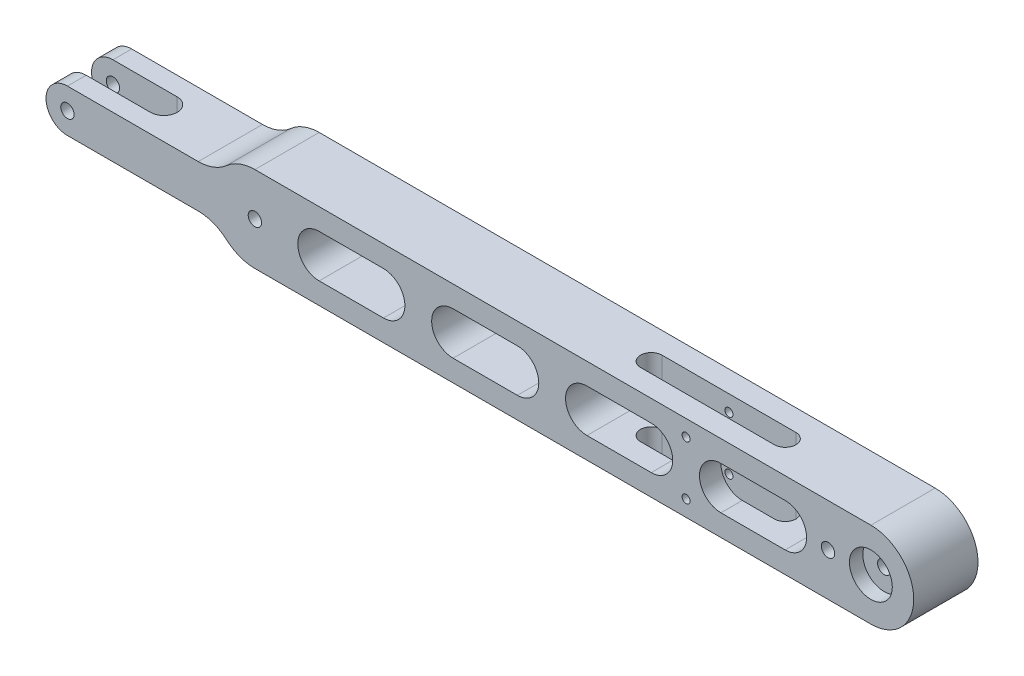
SolidWorks part; units mm, degrees
material "1060 Alloy"
ref_plane "前视基准面" through (0, 0, 0) normal (0, 0, 1) x (1, 0, 0)
ref_plane "上视基准面" through (0, 0, 0) normal (0, 1, 0) x (1, 0, 0)
ref_plane "右视基准面" through (0, 0, 0) normal (1, 0, 0) x (0, 0, -1)
sketch "Sketch1" plane through (0, 0, 0) normal (0, 0, 1) x (1, 0, 0)
  line L0 (0, 0) -> (-70, 0) construction
  line L1 (0, 0) -> (230, 0) construction
  line L2 (0, 16) -> (230, 16)
  line L4 (230, -16) -> (0, -16)
  line L5 (-70, 8) -> (-21.166, 8)
  line L6 (-70, -8) -> (-21.166, -8)
  arc A0 (-70, 8) -> (-70, -8) centre (-70, 0) ccw
  arc A1 (230, -16) -> (230, 16) centre (230, 0) ccw
  arc A2 (-10.583, -12) -> (0, -16) centre (0, 0) ccw
  arc A3 (-10.583, -12) -> (-21.166, -8) centre (-21.166, -24) ccw
  arc A4 (-21.166, 8) -> (-10.583, 12) centre (-21.166, 24) ccw
  arc A5 (0, 16) -> (-10.583, 12) centre (0, 0) ccw
  circle A6 centre (0, 0) radius 2.5
  circle A7 centre (-70, 0) radius 2.5
  point P6 (0, 0)
  dimension "D3" = 16
  dimension "D4" = 32
  dimension "D5" = 16
  dimension "D6" = 5
  dimension "D7" = 5
  dimension "D2" = 230
  dimension "D1" = 70
extrude "Boss-Extrude1" add sketch "Sketch1" along normal mid plane 24
sketch "Sketch2" plane through (0, -8, 0) normal (0, -1, 0) x (1, 0, 0)
  line L0 (-78, 12) -> (-78, -12) construction
  line L1 (-78, -5) -> (-46, -5)
  line L2 (-78, -5) -> (-78, 5)
  line L3 (-78, 5) -> (-46, 5)
  arc A0 (-46, -5) -> (-46, 5) centre (-46, 0) ccw
  point P6 (-44.01, -5)
  point P11 (-78, 0)
  dimension "D1" = 10
  dimension "D2" = 32
extrude "Cut-Extrude1" cut sketch "Sketch2" against normal up to next
sketch "Sketch4" plane through (0, 0, 12) normal (0, 0, 1) x (1, 0, 0)
  line L0 (24, 0) -> (48, 0) construction
  line L1 (24, 8) -> (48, 8)
  line L2 (24, -8) -> (48, -8)
  arc A0 (24, 8) -> (24, -8) centre (24, 0) ccw
  arc A1 (48, -8) -> (48, 8) centre (48, 0) ccw
  point P3 (36, 0)
  dimension "D2" = 8
  dimension "D1" = 24
  dimension "D3" = 24
extrude "Cut-Extrude3" cut sketch "Sketch4" against normal up to next
pattern_linear "LPattern1" count 4 spacing 50 along (1, 0, 0) of "Cut-Extrude3"
sketch "Sketch5" plane through (0, 0, 12) normal (0, 0, 1) x (1, 0, 0)
  circle A0 centre (230, 0) radius 2.5
  circle A1 centre (214, 0) radius 2.5
  point P5 (0, 0)
  dimension "D1" = 5
  dimension "D2" = 5
  dimension "D3" = 16
extrude "Cut-Extrude4" cut sketch "Sketch5" against normal up to next
sketch "Sketch6" plane through (0, 0, 12) normal (0, 0, 1) x (1, 0, 0)
  circle A0 centre (230, 0) radius 8
  dimension "D1" = 16
extrude "Cut-Extrude5" cut sketch "Sketch6" against normal blind 5
mirror "Mirror1" about plane through (0, 0, 0) normal (0, 0, 1) of "Cut-Extrude5"
sketch "Sketch8" plane through (0, -8, 0) normal (0, 1, 0) x (1, 0, 0)
  line L0 (148, 0) -> (124, 0) construction
  line L1 (148, 12) -> (148, -12) construction
  line L2 (124, 12) -> (124, -12) construction
  line L3 (174, 0) -> (198, 0) construction
  line L4 (174, 12) -> (174, -12) construction
  line L5 (198, 12) -> (198, -12) construction
  line L6 (136, 0) -> (186, 0) construction
  line L7 (136, 4) -> (186, 4)
  line L8 (136, -4) -> (186, -4)
  arc A0 (136, 4) -> (136, -4) centre (136, 0) ccw
  arc A1 (186, -4) -> (186, 4) centre (186, 0) ccw
  point P14 (161, 0)
  dimension "D1" = 4
extrude "Cut-Extrude7" cut sketch "Sketch8" against normal through all both and the other way through all
sketch "Sketch9" plane through (0, 0, 12) normal (0, 0, 1) x (1, 0, 0)
  line L0 (156, 0) -> (166, 0) construction
  line L1 (161, 16) -> (161, -16) construction
  line L2 (230, 16) -> (0, 16) construction
  line L3 (0, -16) -> (230, -16) construction
  arc A0 (148, -8) -> (148, 8) centre (148, 0) ccw construction
  arc A1 (174, 8) -> (174, -8) centre (174, 0) ccw construction
  circle A2 centre (161, 10) radius 1.5
  circle A3 centre (161, -10) radius 1.5
  point P18 (162.3973, 16)
  point P19 (161, 0)
  dimension "D3" = 3
  dimension "D4" = 3
  dimension "D1" = 20
  dimension "D2" = 10
extrude "Cut-Extrude8" cut sketch "Sketch9" against normal through all
